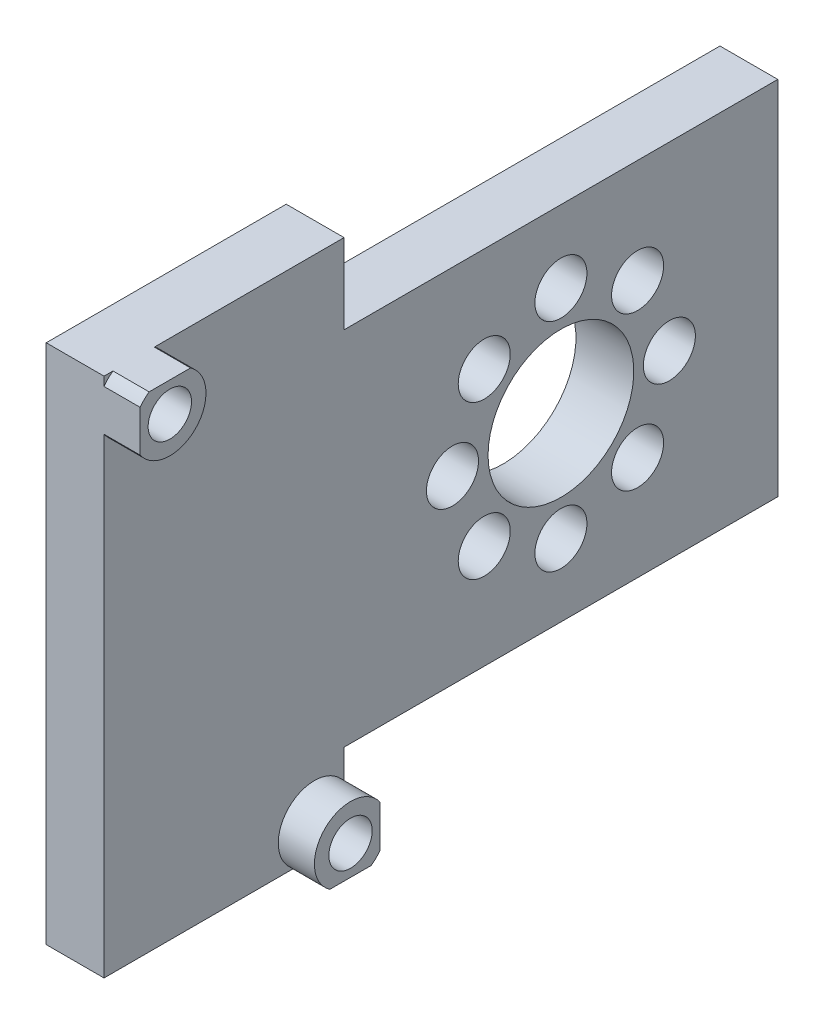
SolidWorks part; units mm, degrees
ref_plane "Front Plane" through (0, 0, 0) normal (1, 0, 0) x (0, 1, 0)
ref_plane "Top Plane" through (0, 0, 0) normal (0, 0, 1) x (0, 1, 0)
ref_plane "Right Plane" through (0, 0, 0) normal (0, 1, 0) x (-1, 0, 0)
sketch "Sketch1" plane through (0, 0, 0) normal (1, 0, 0) x (0, 1, 0)
  line L0 (-20.2883, -7.9375) -> (-22.8918, -7.9375) construction
  line L1 (-22.8917, 10.541) -> (22.8917, 10.541)
  line L2 (-22.8917, 10.541) -> (-22.8917, -10.541)
  line L3 (-22.8917, -10.541) -> (22.8917, -10.541)
  line L4 (22.8917, 10.541) -> (22.8917, -10.541)
  line L5 (-22.8917, 10.541) -> (22.8917, -10.541) construction
  line L6 (-22.8917, -10.541) -> (22.8917, 10.541) construction
  line L7 (-20.2883, -7.9375) -> (-20.2883, -10.541) construction
  line L8 (20.2882, 7.9375) -> (22.8917, 7.9375) construction
  line L9 (20.2882, 7.9375) -> (20.2882, 10.541) construction
  circle A0 centre (-20.2883, -7.9375) radius 1.905
  circle A1 centre (20.2882, 7.9375) radius 1.905
  point P0 (0, 0)
  dimension "D5" = 3.81
  dimension "D3" = 20.2883
  dimension "D1" = 45.7835
  dimension "D2" = 21.082
extrude "Boss-Extrude1" add sketch "Sketch1" along normal blind 5.08
sketch "Sketch2" plane through (5.08, 0, 0) normal (1, 0, 0) x (0, 1, 0)
  line L0 (-22.8917, 10.541) -> (-22.8917, -10.541) construction
  line L1 (18.471, 10.541) -> (22.1055, 10.541)
  line L2 (-22.8917, -6.1202) -> (-22.8917, -9.7548)
  line L3 (-22.1055, -10.541) -> (-18.471, -10.541)
  line L4 (22.8917, 9.7548) -> (22.8917, 6.1202)
  line L5 (-22.8917, 10.541) -> (22.8917, -10.541) construction
  line L6 (-22.8917, -10.541) -> (22.8917, 10.541) construction
  line L7 (-22.8917, -10.541) -> (22.8917, -10.541) construction
  line L8 (22.8917, -10.541) -> (22.8917, 10.541) construction
  line L9 (22.8917, 10.541) -> (-22.8917, 10.541) construction
  arc A0 (-22.8917, -9.7548) -> (-22.1055, -10.541) centre (-20.2883, -7.9375) ccw
  arc A1 (22.8917, 9.7548) -> (22.1055, 10.541) centre (20.2882, 7.9375) ccw
  arc A2 (-18.471, -10.541) -> (-22.8917, -6.1202) centre (-20.2883, -7.9375) ccw
  arc A3 (18.471, 10.541) -> (22.8917, 6.1202) centre (20.2882, 7.9375) ccw
  circle A4 centre (-20.2883, -7.9375) radius 1.905
  circle A5 centre (20.2882, 7.9375) radius 1.905
  point P10 (0, 0)
  dimension "D1" = 6.35
extrude "Boss-Extrude2" add sketch "Sketch2" along normal blind 3.175
sketch "Sketch4" plane through (0, 0, 0) normal (-1, 0, 0) x (0, -1, 0)
  line L0 (0, -29.591) -> (0, 0) construction
  line L1 (15.875, -10.541) -> (-15.875, -10.541)
  line L2 (15.875, -10.541) -> (15.875, -48.641)
  line L3 (15.875, -48.641) -> (-15.875, -48.641)
  line L4 (-15.875, -10.541) -> (-15.875, -48.641)
  line L5 (15.875, -10.541) -> (-15.875, -48.641) construction
  line L6 (15.875, -48.641) -> (-15.875, -10.541) construction
  line L7 (22.8917, -10.541) -> (-22.8917, -10.541) construction
  circle A0 centre (0, -29.591) radius 6.4008
  circle A1 centre (0, -20.066) radius 2.286
  circle A2 centre (6.7352, -22.8558) radius 2.286
  circle A3 centre (9.525, -29.591) radius 2.286
  circle A4 centre (6.7352, -36.3262) radius 2.286
  circle A5 centre (0, -39.116) radius 2.286
  circle A6 centre (-6.7352, -36.3262) radius 2.286
  circle A7 centre (-9.525, -29.591) radius 2.286
  circle A8 centre (-6.7352, -22.8558) radius 2.286
  point P4 (0, -29.591)
  dimension "D1" = 12.8016
  dimension "D2" = 9.525
  dimension "D3" = 4.572
  dimension "D4" = 8
  dimension "D5" = 31.75
  dimension "D6" = 19.05
extrude "Boss-Extrude4" add sketch "Sketch4" against normal blind 5.08
